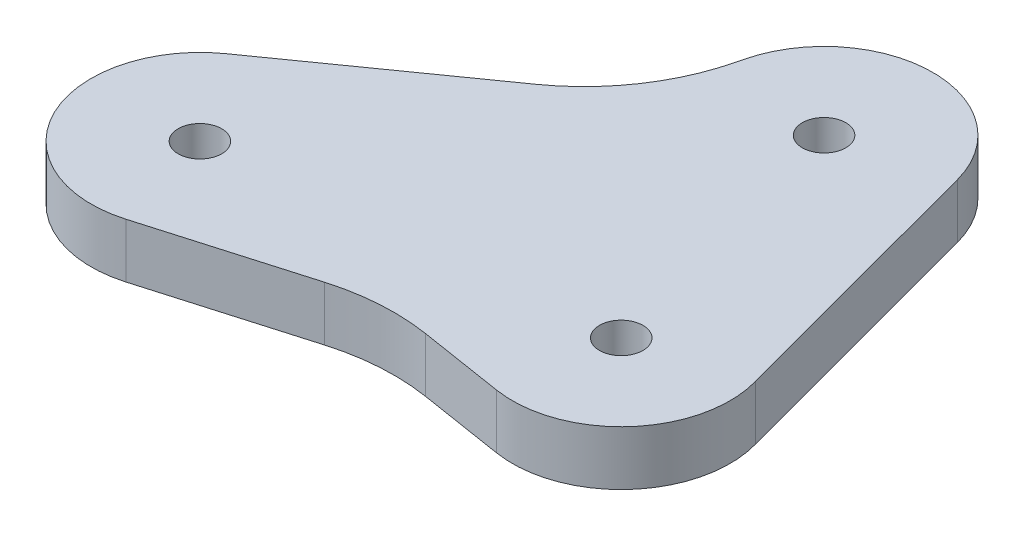
SolidWorks part; units mm, degrees
ref_plane "Ebene vorne" through (0, 0, 0) normal (0, 0, 1) x (1, 0, 0)
ref_plane "Ebene oben" through (0, 0, 0) normal (0, 1, 0) x (1, 0, 0)
ref_plane "Ebene rechts" through (0, 0, 0) normal (1, 0, 0) x (0, 0, -1)
sketch "Skizze1" plane through (0, 0, 0) normal (0, 1, 0) x (1, 0, 0)
  line L0 (20.9847, -13.3576) -> (8.8011, -11.4232)
  line L7 (32.1749, -0.7587) -> (20.9847, -13.3576)
  line L8 (8.8011, -11.4232) -> (-9.6548, -16.7905)
  line L10 (4.1937, 16.8424) -> (6.0339, 24.3446)
  line L11 (32.1749, -0.7587) -> (25.4064, 24.5462)
  line L12 (25.4064, 24.5462) -> (6.0339, 24.3446)
  line L15 (4.1937, 16.8424) -> (-18.2248, 0.9739)
  line L16 (-18.2248, 0.9739) -> (-9.6548, -16.7905)
  circle A0 centre (-12.4473, -7.1883) radius 10
  circle A1 centre (15.746, 21.9623) radius 10
  circle A2 centre (22.5527, -3.4813) radius 10
  circle A3 centre (-12.4473, -7.1883) radius 2
  circle A4 centre (22.5527, -3.4813) radius 2
  circle A5 centre (15.746, 21.9623) radius 2
  dimension "D1" = 20
  dimension "D2" = 20
  dimension "D3" = 20
  dimension "D4" = 35
  dimension "D5" = 4
  dimension "D6" = 4
  dimension "D7" = 4
extrude "Aufsatz-Linear austragen1" add sketch "Skizze1" along normal blind 5
fillet "Verrundung1" radius 19 1 edges at (4.1937, 2.5, -16.8424)
fillet "Verrundung2" radius 20 1 edges at (8.8011, 2.5, 11.4232)
